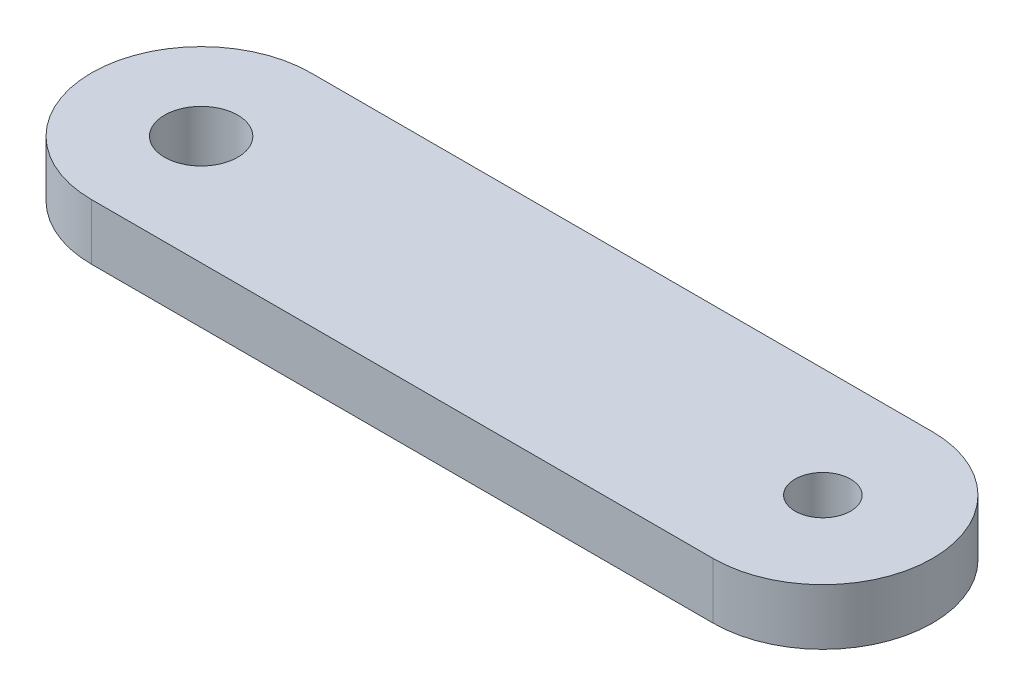
SolidWorks part; units mm, degrees
ref_plane "Front" through (0, 0, 0) normal (0, 0, 1) x (1, 0, 0)
ref_plane "Top" through (0, 0, 0) normal (0, 1, 0) x (1, 0, 0)
ref_plane "Right" through (0, 0, 0) normal (1, 0, 0) x (0, 0, -1)
sketch "Sketch1" plane through (0, 0, 0) normal (0, 1, 0) x (1, 0, 0)
  line L1 (-53.975, 9.525) -> (0, 9.525)
  line L3 (-53.975, -9.525) -> (0, -9.525)
  arc A0 (-53.975, 9.525) -> (-53.975, -9.525) centre (-53.975, 0) ccw
  arc A1 (0, 9.525) -> (0, -9.525) centre (0, 0) cw
  circle A2 centre (-53.975, 0) radius 2.3495 construction
  circle A7 centre (0, 0) radius 2.5654
  circle A8 centre (-53.975, 0) radius 3.175
  dimension "D2" = 5.1308
  dimension "D3" = 6.35
  dimension "D1" = 9.525
extrude "Boss-Extrude1" add sketch "Sketch1" along normal up to surface (4.8641 mm away) contours A0 L3 A1 L1
sketch "Sketch3" plane through (0, 4.8641, 0) normal (0, 1, 0) x (1, 0, 0)
  circle A0 centre (-53.975, 0) radius 3.175
  circle A1 centre (0, 0) radius 2.413
  arc A2 (-53.975, 9.525) -> (-53.975, -9.525) centre (-53.975, 0) ccw construction
  dimension "D1" = 6.35
  dimension "D2" = 4.826
extrude "Cut-Extrude1" cut sketch "Sketch3" against normal through all
